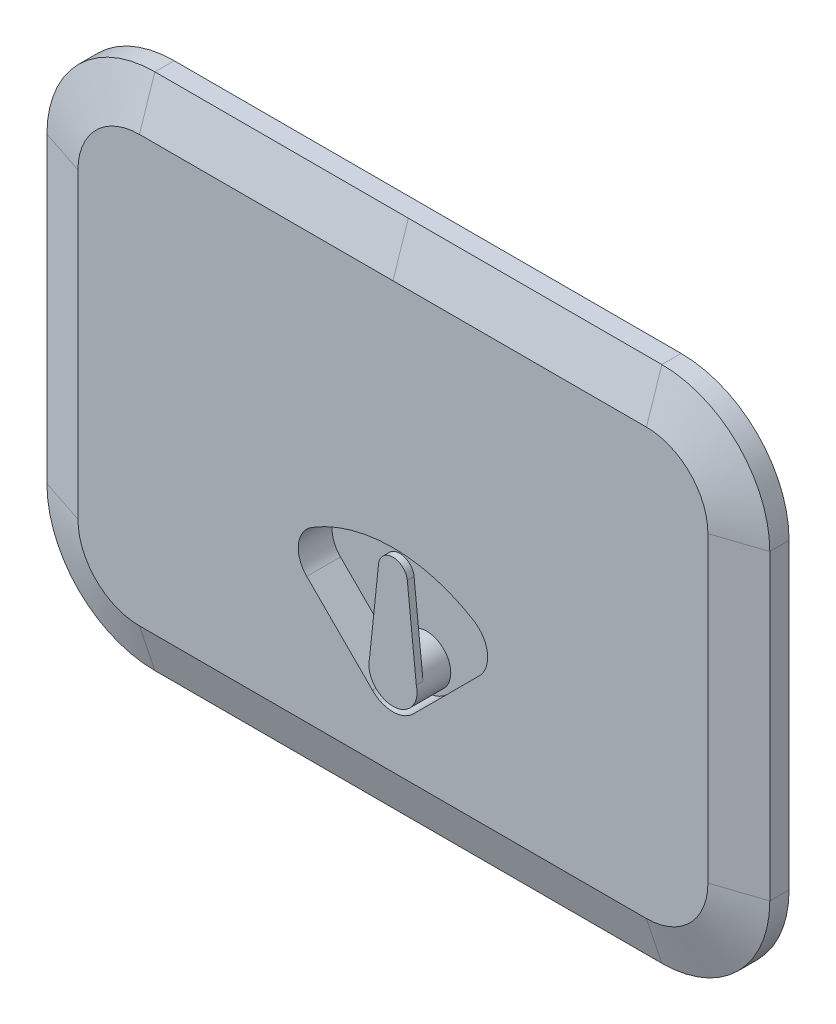
SolidWorks part; units mm, degrees
material "ABS"
ref_plane "Front Plane" through (0, 0, 0) normal (0, 0, 1) x (1, 0, 0)
ref_plane "Top Plane" through (0, 0, 0) normal (0, 1, 0) x (1, 0, 0)
ref_plane "Right Plane" through (0, 0, 0) normal (1, 0, 0) x (0, 0, -1)
sketch "Sketch1" plane through (0, 0, 0) normal (0, 0, 1) x (1, 0, 0)
  line L1 (-131.5, -134.5) -> (131.5, -134.5)
  line L2 (-187.5, -78.5) -> (-187.5, 78.5)
  line L3 (-131.5, 134.5) -> (131.5, 134.5)
  line L4 (187.5, -78.5) -> (187.5, 78.5)
  line L5 (-187.5, -134.5) -> (187.5, 134.5) construction
  line L6 (-187.5, 134.5) -> (187.5, -134.5) construction
  arc A0 (187.5, 78.5) -> (131.5, 134.5) centre (131.5, 78.5) ccw
  arc A1 (131.5, -134.5) -> (187.5, -78.5) centre (131.5, -78.5) ccw
  arc A2 (-131.5, -134.5) -> (-187.5, -78.5) centre (-131.5, -78.5) cw
  arc A3 (-187.5, 78.5) -> (-131.5, 134.5) centre (-131.5, 78.5) cw
  point P0 (0, 0)
  dimension "D3" = 56
  dimension "D1" = 269
  dimension "D2" = 375
extrude "Boss-Extrude1" add sketch "Sketch1" along normal blind 18
sketch "Sketch2" plane through (0, 0, 0) normal (1, 0, 0) x (0, 0, -1)
  line L0 (-18, 110.3927) -> (-10, 134.5)
  line L1 (-18, 134.5) -> (-18, 78.5) construction
  line L2 (-18, 134.5) -> (0, 134.5) construction
  line L3 (-10, 134.5) -> (0, 134.5) construction
  line L4 (-18, 110.3927) -> (-18, 134.5)
  line L5 (-18, 134.5) -> (-10, 134.5)
  dimension "D1" = 25.4
  dimension "D2" = 10
sketch "Sketch3" plane through (0, 0, 18) normal (0, 0, 1) x (1, 0, 0)
  line L4 (131.5, 134.5) -> (-131.5, 134.5)
  line L5 (-187.5, 78.5) -> (-187.5, -78.5)
  line L6 (-131.5, -134.5) -> (131.5, -134.5)
  line L7 (187.5, -78.5) -> (187.5, 78.5)
  line L8 (131.5, 134.5) -> (-131.5, 134.5)
  line L9 (-187.5, 78.5) -> (-187.5, -78.5)
  line L10 (-131.5, -134.5) -> (131.5, -134.5)
  line L11 (187.5, -78.5) -> (187.5, 78.5)
  arc A4 (187.5, 78.5) -> (131.5, 134.5) centre (131.5, 78.5) ccw
  arc A5 (-131.5, 134.5) -> (-187.5, 78.5) centre (-131.5, 78.5) ccw
  arc A6 (-187.5, -78.5) -> (-131.5, -134.5) centre (-131.5, -78.5) ccw
  arc A7 (131.5, -134.5) -> (187.5, -78.5) centre (131.5, -78.5) ccw
  arc A8 (187.5, 78.5) -> (131.5, 134.5) centre (131.5, 78.5) ccw
  arc A9 (-131.5, 134.5) -> (-187.5, 78.5) centre (-131.5, 78.5) ccw
  arc A10 (-187.5, -78.5) -> (-131.5, -134.5) centre (-131.5, -78.5) ccw
  arc A11 (131.5, -134.5) -> (187.5, -78.5) centre (131.5, -78.5) ccw
  dimension "D1" = 0
sweep "Cut-Sweep1" cut profiles "Sketch2" path "Sketch3"
sketch "Sketch4" plane through (0, 0, 0) normal (0, 0, -1) x (-1, 0, 0)
  line L1 (113.5, 96) -> (-113.5, 96)
  line L2 (145.5, 64) -> (145.5, -64)
  line L3 (113.5, -96) -> (-113.5, -96)
  line L4 (-145.5, 64) -> (-145.5, -64)
  line L5 (145.5, 96) -> (-145.5, -96) construction
  line L6 (145.5, -96) -> (-145.5, 96) construction
  arc A0 (113.5, 96) -> (145.5, 64) centre (113.5, 64) cw
  arc A1 (145.5, -64) -> (113.5, -96) centre (113.5, -64) cw
  arc A2 (-145.5, 64) -> (-113.5, 96) centre (-113.5, 64) cw
  arc A3 (-145.5, -64) -> (-113.5, -96) centre (-113.5, -64) ccw
  point P0 (0, 0)
  dimension "D3" = 32
  dimension "D4" = 32
  dimension "D1" = 291
  dimension "D2" = 192
extrude "Boss-Extrude2" add sketch "Sketch4" along normal blind 24.5
sketch "Sketch5" plane through (0, 0, 18) normal (0, 0, 1) x (1, 0, 0)
  line L0 (-131.5, -134.5) -> (131.5, -134.5) construction
  line L1 (10.6066, -78.8934) -> (44.7214, -44.7786)
  line L2 (-10.6066, -78.8934) -> (-44.7214, -44.7786)
  line L3 (-56.5685, -32.9315) -> (56.5685, -32.9315) construction
  line L4 (0, -32.9315) -> (0, -89.5) construction
  arc A0 (41.9874, -21.404) -> (-41.9874, -21.404) centre (0, -89.5) ccw
  arc A1 (-10.6066, -78.8934) -> (10.6066, -78.8934) centre (0, -68.2868) ccw
  arc A2 (44.7214, -44.7786) -> (41.9874, -21.404) centre (34.1148, -34.172) ccw
  arc A3 (-44.7214, -44.7786) -> (-41.9874, -21.404) centre (-34.1148, -34.172) cw
  dimension "D1" = 45
  dimension "D2" = 160
  dimension "D4" = 15
  dimension "D3" = 90
extrude "Cut-Extrude1" cut sketch "Sketch5" against normal blind 17.5
sketch "Sketch6" plane through (0, 0, 0.5) normal (0, 0, 1) x (1, 0, 0)
  circle A0 centre (0, -68.2868) radius 12.5
  dimension "D1" = 25
extrude "Boss-Extrude3" add sketch "Sketch6" along normal blind 14
sketch "Sketch7" plane through (0, 0, 14.5) normal (0, 0, 1) x (1, 0, 0)
  line L0 (0, -68.2868) -> (0, -21.2868) construction
  line L1 (-7.4595, -20.5085) -> (-12.1294, -65.2655)
  line L2 (7.4595, -20.5085) -> (12.1294, -65.2655)
  circle A0 centre (0, -68.2868) radius 12.5 construction
  arc A1 (7.4595, -20.5085) -> (-7.4595, -20.5085) centre (0, -21.2868) ccw
  arc A2 (-12.1294, -65.2655) -> (12.1294, -65.2655) centre (0, -68.2868) ccw
  dimension "D1" = 15
  dimension "D2" = 47
  dimension "D3" = 45
extrude "Boss-Extrude4" add sketch "Sketch7" along normal up to surface (3.5 mm away) up to face at (0, -46.8863, 18)
sketch "Sketch8" plane through (0, 0, -24.5) normal (0, 0, -1) x (-1, 0, 0)
  line L0 (-3.3527, 0) -> (-135.8461, -84.3148)
  line L1 (0, -2.1336) -> (-133.1946, -86.8946)
  line L14 (-143.7, 64) -> (-143.7, -64)
  line L15 (-113.5, -94.2) -> (113.5, -94.2)
  line L16 (143.7, -64) -> (143.7, 64)
  line L17 (113.5, 94.2) -> (-113.5, 94.2)
  line L18 (-135.8461, 84.3148) -> (-3.3527, 0)
  line L19 (133.1946, 86.8946) -> (0, 2.1336)
  line L20 (-133.1946, 86.8946) -> (0, 2.1336)
  line L21 (135.8461, 84.3148) -> (3.3527, 0)
  line L22 (3.3527, 0) -> (135.8461, -84.3148)
  line L23 (0, -2.1336) -> (133.1946, -86.8946)
  arc A15 (-143.7, -64) -> (-113.5, -94.2) centre (-113.5, -64) ccw
  arc A16 (113.5, -94.2) -> (143.7, -64) centre (113.5, -64) ccw
  arc A17 (143.7, 64) -> (113.5, 94.2) centre (113.5, 64) ccw
  arc A18 (-113.5, 94.2) -> (-143.7, 64) centre (-113.5, 64) ccw
  point P0 (134.5695, 85.636)
  point P1 (-134.5695, 85.636)
  point P9 (134.5695, -85.636)
  point P13 (-113.5, -64)
  point P14 (-145.5, -64)
  point P15 (-113.5, -96)
  point P16 (113.5, 64)
  point P17 (145.5, 64)
  point P18 (115.2168, 101.7098)
  point P20 (-100.2195, 109.9485)
  point P21 (145.5, -64)
  point P23 (113.5, -64)
  point P24 (113.5, -96)
  point P28 (-145.5, 64)
  point P30 (-113.5, 64)
  point P49 (-134.5695, -85.636)
extrude "Cut-Extrude4" [suppressed] cut sketch "Sketch8" against normal blind 25 contours L18 A18 L14 A15 L0 | L16 A17 L21 L22 A16
sketch "Sketch9" plane through (0, 0, -24.5) normal (0, 0, -1) x (-1, 0, 0)
  line L8 (113.5, 92.55) -> (-113.5, 92.55)
  line L9 (-142.05, 64) -> (-142.05, -64)
  line L10 (-113.5, -92.55) -> (113.5, -92.55)
  line L11 (142.05, -64) -> (142.05, 64)
  line L12 (113.5, 92.55) -> (-113.5, 92.55)
  line L13 (-142.05, 64) -> (-142.05, -64)
  line L14 (-113.5, -92.55) -> (113.5, -92.55)
  line L15 (142.05, -64) -> (142.05, 64)
  arc A8 (142.05, 64) -> (113.5, 92.55) centre (113.5, 64) ccw
  arc A9 (-113.5, 92.55) -> (-142.05, 64) centre (-113.5, 64) ccw
  arc A10 (-142.05, -64) -> (-113.5, -92.55) centre (-113.5, -64) ccw
  arc A11 (113.5, -92.55) -> (142.05, -64) centre (113.5, -64) ccw
  arc A12 (142.05, 64) -> (113.5, 92.55) centre (113.5, 64) ccw
  arc A13 (-113.5, 92.55) -> (-142.05, 64) centre (-113.5, 64) ccw
  arc A14 (-142.05, -64) -> (-113.5, -92.55) centre (-113.5, -64) ccw
  arc A15 (113.5, -92.55) -> (142.05, -64) centre (113.5, -64) ccw
  dimension "D1" = 3.45
extrude "Cut-Extrude6" cut sketch "Sketch9" against normal blind 23.5
